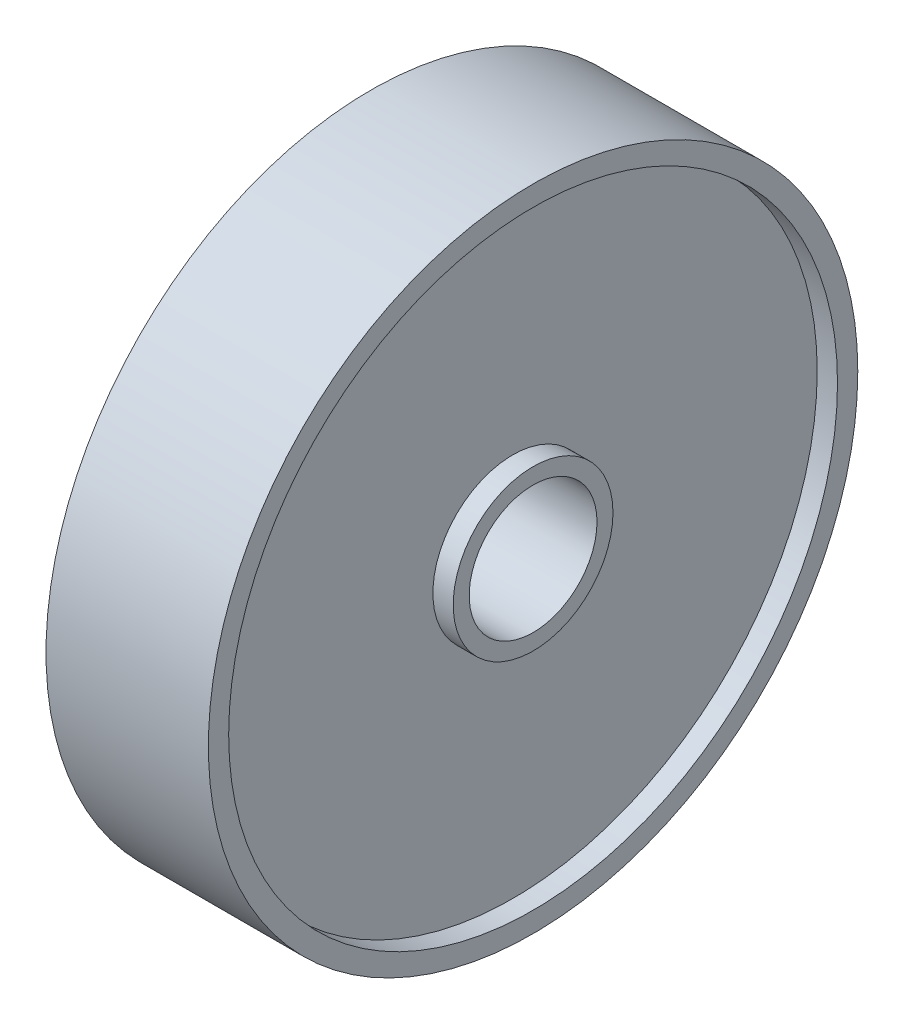
SolidWorks part; units mm, degrees
material "AISI 1020"
ref_plane "Front Plane" through (0, 0, 0) normal (0, 0, 1) x (1, 0, 0)
ref_plane "Top Plane" through (0, 0, 0) normal (0, 1, 0) x (1, 0, 0)
ref_plane "Right Plane" through (0, 0, 0) normal (1, 0, 0) x (0, 0, -1)
sketch "Sketch1" plane through (0, 0, 0) normal (1, 0, 0) x (0, 0, -1)
  circle A0 centre (0, 0) radius 101.6
  circle A1 centre (0, 0) radius 20
  dimension "D1" = 203.2
  dimension "D2" = 40
extrude "Boss-Extrude1" add sketch "Sketch1" along normal blind 50.8
sketch "Sketch2" plane through (0, 0, 0) normal (-1, 0, 0) x (0, 0, 1)
  circle A0 centre (0, 0) radius 95.25
  circle A1 centre (0, 0) radius 25
  dimension "D1" = 190.5
  dimension "D2" = 50
extrude "Cut-Extrude1" cut sketch "Sketch2" against normal blind 6.35
sketch "Sketch3" plane through (50.8, 0, 0) normal (1, 0, 0) x (0, 0, -1)
  circle A0 centre (0, 0) radius 95.25
  circle A1 centre (0, 0) radius 25
  dimension "D1" = 190.5
  dimension "D2" = 50
extrude "Cut-Extrude2" cut sketch "Sketch3" against normal blind 6.35
